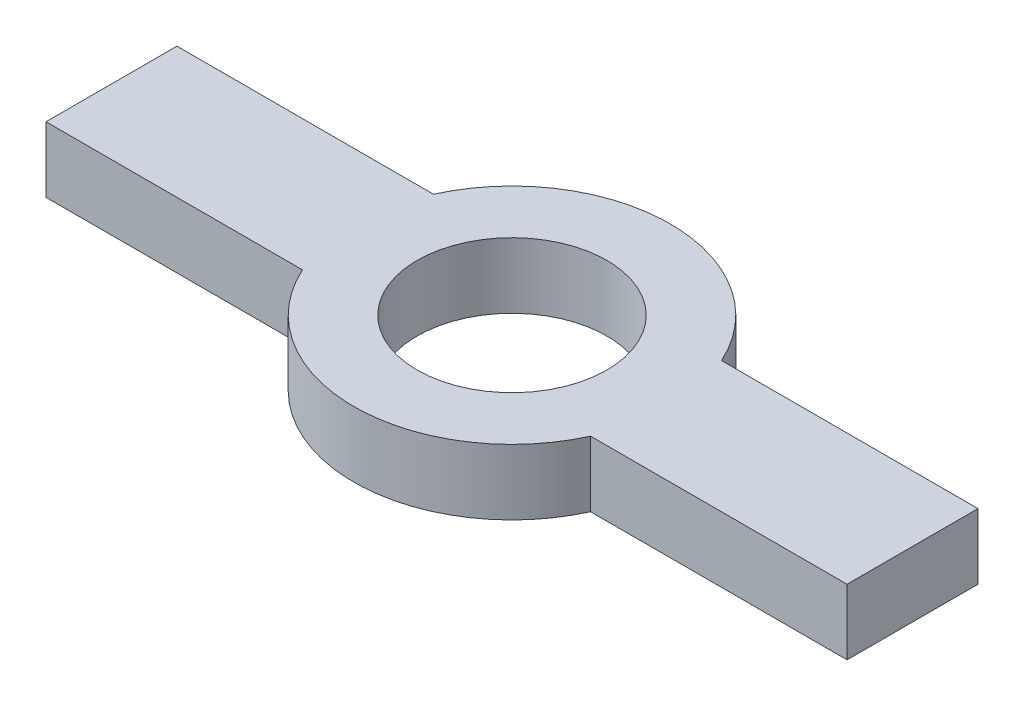
SolidWorks part; units mm, degrees
ref_plane "Front" through (0, 0, 0) normal (0, 0, 1) x (1, 0, 0)
ref_plane "Top" through (0, 0, 0) normal (0, 1, 0) x (1, 0, 0)
ref_plane "Right" through (0, 0, 0) normal (1, 0, 0) x (0, 0, -1)
sketch "Sketch1" plane through (0, 0, 0) normal (0, 1, 0) x (1, 0, 0)
  circle A0 centre (0, 0) radius 4.35
  circle A1 centre (0, 0) radius 7.25
  dimension "D1" = 8.7
  dimension "D2" = 14.5
extrude "Boss-Extrude1" add sketch "Sketch1" along normal blind 3
sketch "Sketch2" plane through (0, 0, 0) normal (0, 1, 0) x (1, 0, 0)
  line L0 (4.35, 0) -> (4.35, 3)
  line L1 (-50, 0) -> (50, 0) construction
  line L2 (0, -50) -> (0, 50) construction
  line L3 (4.35, 3) -> (18.35, 3)
  line L4 (4.35, 3) -> (4.35, -3)
  line L5 (4.35, -3) -> (18.35, -3)
  line L6 (18.35, 3) -> (18.35, -3)
  line L7 (-4.35, -3) -> (-18.35, -3)
  line L8 (-4.35, 3) -> (-4.35, -3)
  line L9 (-4.35, 0) -> (-4.35, 3)
  line L10 (-18.35, 3) -> (-18.35, -3)
  line L11 (-4.35, 3) -> (-18.35, 3)
  circle A0 centre (0, 0) radius 4.35 construction
  dimension "D1" = 3
  dimension "D2" = 6
  dimension "D3" = 14
extrude "Boss-Extrude2" add sketch "Sketch2" along normal blind 3 contours L6 L3 L0 L4 L5 | L8 L11 L10 L7
